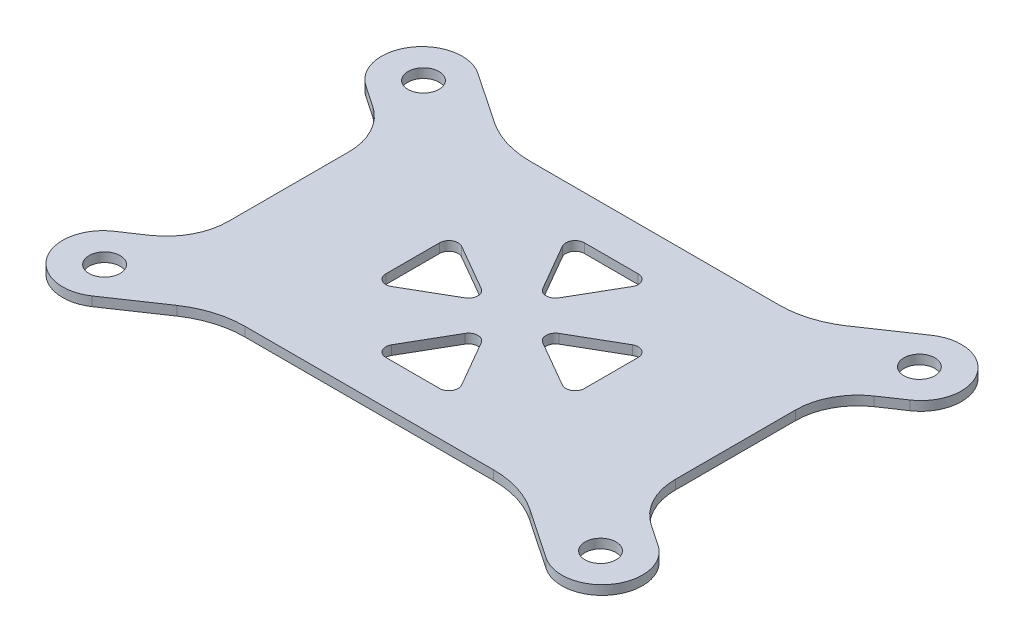
SolidWorks part; units mm, degrees
ref_plane "Front Plane" through (0, 0, 0) normal (0, 0, 1) x (1, 0, 0)
ref_plane "Top Plane" through (0, 0, 0) normal (0, 1, 0) x (1, 0, 0)
ref_plane "Right Plane" through (0, 0, 0) normal (1, 0, 0) x (0, 0, -1)
sketch "Sketch1" plane through (0, 0, 0) normal (0, 1, 0) x (1, 0, 0)
  line L1 (-36, -23) -> (36, -23)
  line L2 (-36, -23) -> (-36, 23)
  line L3 (-36, 23) -> (36, 23)
  line L4 (36, -23) -> (36, 23)
  line L5 (-36, -23) -> (36, 23) construction
  line L6 (-36, 23) -> (36, -23) construction
  point P0 (0, 0)
  dimension "D1" = 72
  dimension "D2" = 46
extrude "Boss-Extrude1" add sketch "Sketch1" along normal blind 1.5
sketch "Sketch2" plane through (0, 0, 0) normal (0, -1, 0) x (-1, 0, 0)
  line L0 (0, 0) -> (-36, -23) construction
  line L1 (-36, -23) -> (-93.2441, -59.5726) construction
  line L2 (0, 0) -> (40.2135, 25.6919) construction
  line L3 (0, 0) -> (36, -23) construction
  line L4 (36, -23) -> (90.4744, -57.8031) construction
  line L5 (0, 0) -> (-36, 23) construction
  line L6 (-36, 23) -> (-93.2441, 59.5726) construction
  line L8 (43.8554, -20.3081) -> (27.3303, -9.1297)
  line L9 (36.5715, -31.0758) -> (20.0465, -19.8974)
  line L10 (27.3303, -9.1297) -> (20.0465, -19.8974)
  line L11 (43.8554, 20.3081) -> (27.8679, 9.4933)
  line L12 (36.5715, 31.0758) -> (20.584, 20.261)
  line L13 (27.8679, 9.4933) -> (20.584, 20.261)
  line L14 (45.691, 29.1915) -> (152.7787, 97.6086) construction
  line L15 (-36.5715, 31.0758) -> (-20.3033, 20.0712)
  line L16 (-43.8554, 20.3081) -> (-27.5872, 9.3034)
  line L17 (-20.3033, 20.0712) -> (-27.5872, 9.3034)
  line L18 (-43.8554, -20.3081) -> (-27.378, -9.1619)
  line L19 (-36.5715, -31.0758) -> (-20.0941, -19.9297)
  line L20 (-27.378, -9.1619) -> (-20.0941, -19.9297)
  arc A0 (-43.8554, -20.3081) -> (-36.5715, -31.0758) centre (-40.2135, -25.6919) ccw
  arc A1 (36.5715, -31.0758) -> (43.8554, -20.3081) centre (40.2135, -25.6919) ccw
  arc A2 (43.8554, 20.3081) -> (36.5715, 31.0758) centre (40.2135, 25.6919) ccw
  arc A3 (-36.5715, 31.0758) -> (-43.8554, 20.3081) centre (-40.2135, 25.6919) ccw
  dimension "D1" = 5
  dimension "D2" = 5
  dimension "D3" = 5
  dimension "D4" = 5
extrude "Boss-Extrude2" add sketch "Sketch2" against normal blind 1.5
fillet "Fillet1" radius 10 4 edges at (36, 0.75, 14.9943) (36, 0.75, -14.9943) (-36, 0.75, 14.9943) (-36, 0.75, -14.9943)
fillet "Fillet2" radius 15 4 edges at (-24.633, 0.75, -23) (24.633, 0.75, -23) (24.633, 0.75, 23) (-24.633, 0.75, 23)
sketch "Sketch4" plane through (0, 1.5, 0) normal (0, 1, 0) x (1, 0, 0)
  circle A2 centre (-39.9543, -25.6886) radius 2.5
  circle A3 centre (39.9543, 25.6886) radius 2.5
  circle A4 centre (-39.9543, 25.6886) radius 2.5
  circle A5 centre (39.9543, -25.6886) radius 2.5
  point P7 (0, 0)
  point P14 (0, 0)
  dimension "D1" = 47.5
  dimension "D2" = 47.5
  dimension "D3" = 47.5
  dimension "D4" = 47.5
extrude "Cut-Extrude1" cut sketch "Sketch4" against normal through all
sketch "Sketch5" plane through (0, 1.5, 0) normal (0, 1, 0) x (1, 0, 0)
  line L1 (1.299, 6.25) -> (5.6292, 13.75)
  line L2 (4.3301, 16) -> (-4.3301, 16)
  line L3 (-5.6292, 13.75) -> (-1.299, 6.25)
  line L4 (-1.299, -6.25) -> (-5.6292, -13.75)
  line L5 (-4.3301, -16) -> (4.3301, -16)
  line L6 (5.6292, -13.75) -> (1.299, -6.25)
  line L7 (-6.25, 1.299) -> (-13.75, 5.6292)
  line L8 (-16, 4.3301) -> (-16, -4.3301)
  line L9 (-13.75, -5.6292) -> (-6.25, -1.299)
  line L10 (6.25, -1.299) -> (13.75, -5.6292)
  line L11 (16, -4.3301) -> (16, 4.3301)
  line L12 (13.75, 5.6292) -> (6.25, 1.299)
  circle A0 centre (0, 12) radius 4 construction
  circle A1 centre (0, -12) radius 4 construction
  circle A2 centre (-12, 0) radius 4 construction
  circle A3 centre (12, 0) radius 4 construction
  arc A4 (16, 4.3301) -> (13.75, 5.6292) centre (14.5, 4.3301) ccw
  arc A5 (13.75, -5.6292) -> (16, -4.3301) centre (14.5, -4.3301) ccw
  arc A6 (6.25, -1.299) -> (6.25, 1.299) centre (7, 0) cw
  arc A7 (5.6292, 13.75) -> (4.3301, 16) centre (4.3301, 14.5) ccw
  arc A8 (-4.3301, 16) -> (-5.6292, 13.75) centre (-4.3301, 14.5) ccw
  arc A9 (1.299, 6.25) -> (-1.299, 6.25) centre (0, 7) cw
  arc A10 (-1.299, -6.25) -> (1.299, -6.25) centre (0, -7) cw
  arc A11 (4.3301, -16) -> (5.6292, -13.75) centre (4.3301, -14.5) ccw
  arc A12 (-5.6292, -13.75) -> (-4.3301, -16) centre (-4.3301, -14.5) ccw
  arc A13 (-6.25, 1.299) -> (-6.25, -1.299) centre (-7, 0) cw
  arc A14 (-13.75, 5.6292) -> (-16, 4.3301) centre (-14.5, 4.3301) ccw
  arc A15 (-16, -4.3301) -> (-13.75, -5.6292) centre (-14.5, -4.3301) ccw
  point P27 (4, 0)
  point P34 (0, 4)
  point P37 (0, -4)
  point P44 (-4, 0)
  dimension "D9" = 1.5
  dimension "D1" = 4
  dimension "D2" = 16
  dimension "D3" = 4
  dimension "D4" = 16
  dimension "D5" = 4
  dimension "D6" = 16
  dimension "D7" = 4
  dimension "D8" = 16
extrude "Cut-Extrude2" cut sketch "Sketch5" against normal through all
